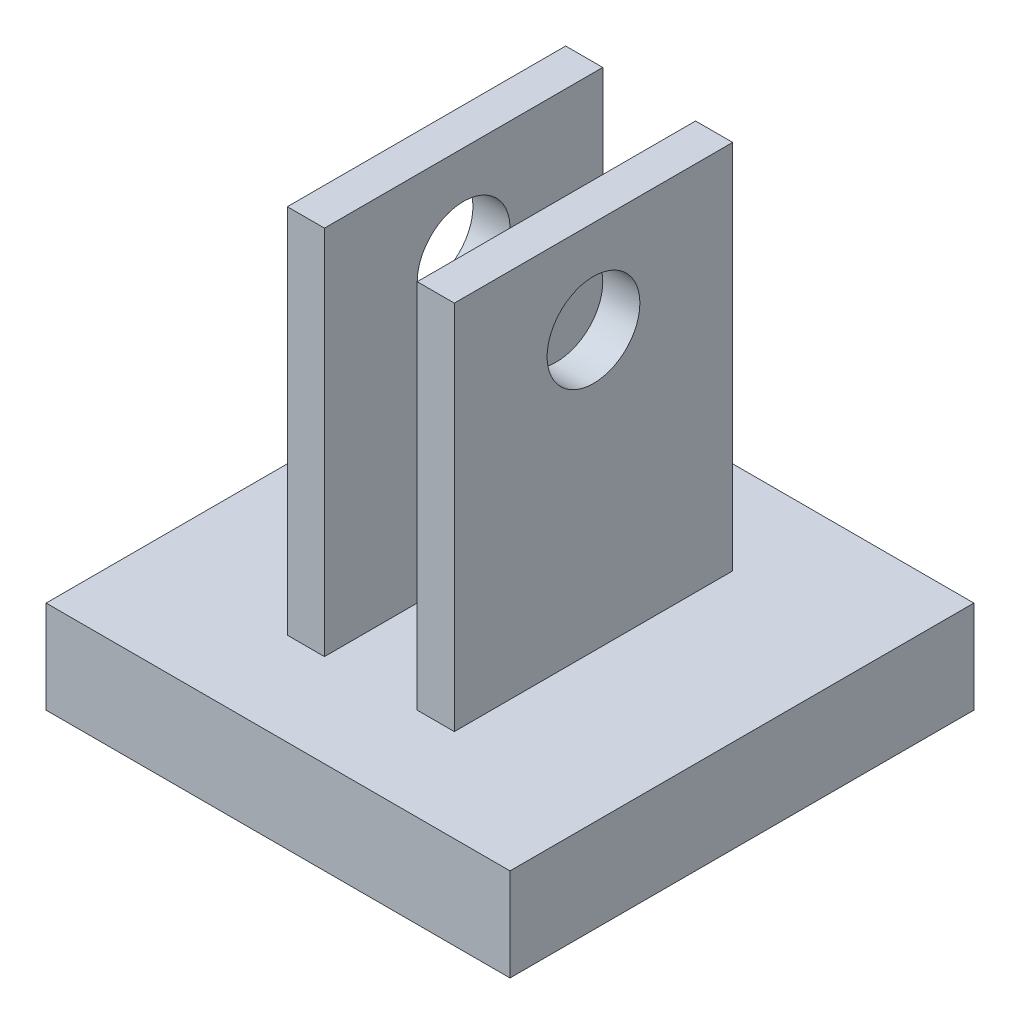
SolidWorks part; units mm, degrees
ref_plane "Front Plane" through (0, 0, 0) normal (0, 0, 1) x (1, 0, 0)
ref_plane "Top Plane" through (0, 0, 0) normal (0, 1, 0) x (1, 0, 0)
ref_plane "Right Plane" through (0, 0, 0) normal (1, 0, 0) x (0, 0, -1)
sketch "Sketch1" plane through (0, 0, 0) normal (0, 1, 0) x (1, 0, 0)
  line L1 (-12.5, 12.5) -> (12.5, 12.5)
  line L2 (-12.5, 12.5) -> (-12.5, -12.5)
  line L3 (-12.5, -12.5) -> (12.5, -12.5)
  line L4 (12.5, 12.5) -> (12.5, -12.5)
  line L5 (-12.5, 12.5) -> (12.5, -12.5) construction
  line L6 (-12.5, -12.5) -> (12.5, 12.5) construction
  point P0 (0, 0)
  dimension "D1" = 25
  dimension "D2" = 25
extrude "Boss-Extrude1" add sketch "Sketch1" along normal blind 5
sketch "Sketch2" plane through (0, 5, 0) normal (0, 1, 0) x (1, 0, 0)
ref_plane "Plane1" through (0, 0, 0) normal (1, 0, 0) x (0, 0, -1)
sketch "Sketch10" plane through (0, 5, 0) normal (0, 1, 0) x (1, 0, 0)
  line L2 (2.5, 7.5) -> (4.5, 7.5)
  line L3 (2.5, 7.5) -> (2.5, -7.5)
  line L4 (2.5, -7.5) -> (4.5, -7.5)
  line L5 (4.5, 7.5) -> (4.5, -7.5)
  point P2 (3.5, 0)
  dimension "D1" = 15
  dimension "D2" = 2
extrude "Boss-Extrude3" add sketch "Sketch10" along normal blind 20 contours L3 L2 L5 L4
sketch "Sketch12" plane through (0, 5, 0) normal (0, 1, 0) x (1, 0, 0)
  line L0 (0, 12.5) -> (0, -12.5) construction
  line L1 (12.5, 12.5) -> (-12.5, 12.5) construction
  line L2 (-12.5, -12.5) -> (12.5, -12.5) construction
mirror "Mirror1" about plane through (0, 0, 0) normal (1, 0, 0) of bodies 105
sketch "Sketch13" plane through (-4.5, 0, 0) normal (-1, 0, 0) x (0, 0, 1)
  line L0 (0, 25) -> (0, 15) construction
  line L1 (-7.5, 25) -> (7.5, 25) construction
  circle A0 centre (0, 20) radius 2.5
  dimension "D1" = 5
extrude "Cut-Extrude3" cut sketch "Sketch13" against normal through all
